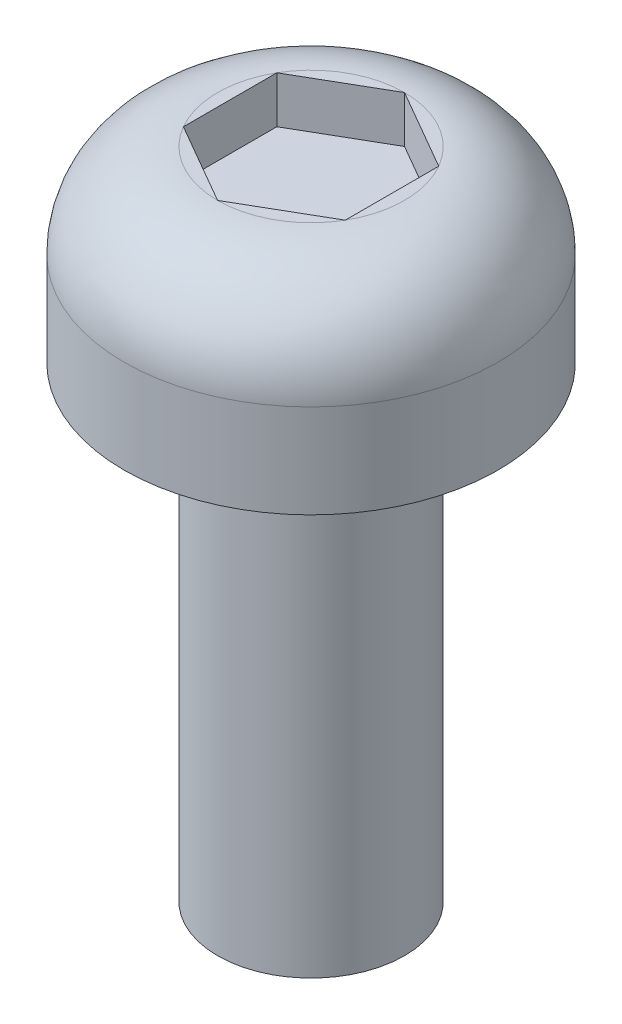
SolidWorks part; units mm, degrees
ref_plane "Front Plane" through (0, 0, 0) normal (0, 0, 1) x (1, 0, 0)
ref_plane "Top Plane" through (0, 0, 0) normal (0, 1, 0) x (1, 0, 0)
ref_plane "Right Plane" through (0, 0, 0) normal (1, 0, 0) x (0, 0, -1)
sketch "Sketch1" plane through (0, 0, 0) normal (0, 1, 0) x (1, 0, 0)
  circle A0 centre (0, 0) radius 1
  dimension "D1" = 2
extrude "Boss-Extrude1" add sketch "Sketch1" along normal blind 5
sketch "Sketch2" plane through (0, 5, 0) normal (0, 1, 0) x (1, 0, 0)
  circle A0 centre (0, 0) radius 2
  dimension "D1" = 4
extrude "Boss-Extrude2" add sketch "Sketch2" along normal blind 2
fillet "Fillet1" radius 1 1 edges at (0, 7, 2)
sketch "Sketch3" plane through (0, 7, 0) normal (0, 1, 0) x (1, 0, 0)
  line L0 (0, -1) -> (0, 1)
  line L1 (-0.866, -0.5) -> (0.866, 0.5)
  line L2 (0.866, -0.5) -> (-0.866, 0.5)
  line L3 (0, 1) -> (-0.866, 0.5)
  line L4 (-0.866, 0.5) -> (-0.866, -0.5)
  line L5 (-0.866, -0.5) -> (0, -1)
  line L6 (0, -1) -> (0.866, -0.5)
  line L7 (0.866, -0.5) -> (0.866, 0.5)
  line L8 (0.866, 0.5) -> (0, 1)
  circle A0 centre (0, 0) radius 1 construction
  point P7 (0, 0)
  point P11 (0, 0)
  point P14 (0, 0)
  point P15 (0, 0)
  point P17 (0, 0)
  dimension "D1" = 60
  dimension "D2" = 60
extrude "Cut-Extrude1" cut sketch "Sketch3" against normal blind 0.5 contours L0 L3 L2 | L2 L4 L1 | L1 L5 L0 | L0 L6 L2 | L2 L7 L1 | L1 L8 L0
